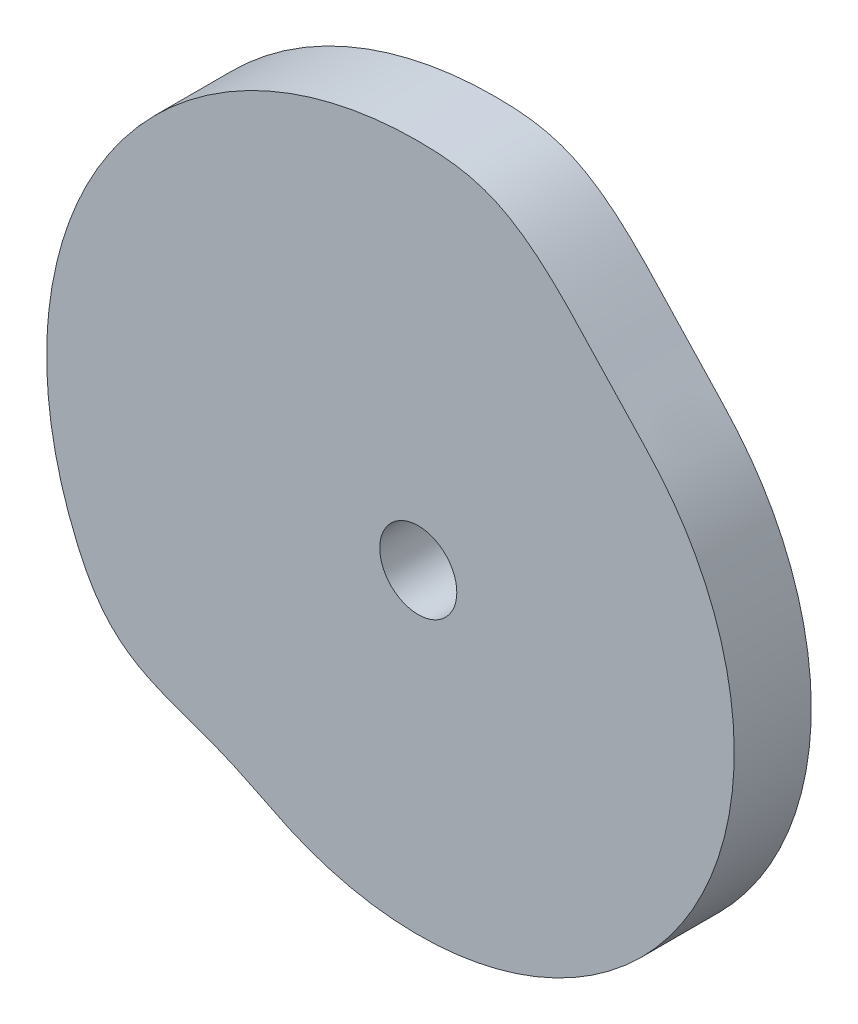
SolidWorks part; units mm, degrees
ref_plane "前视基准面" through (0, 0, 0) normal (0, 0, 1) x (1, 0, 0)
ref_plane "上视基准面" through (0, 0, 0) normal (0, 1, 0) x (1, 0, 0)
ref_plane "右视基准面" through (0, 0, 0) normal (1, 0, 0) x (0, 0, -1)
other "Configuration Table"
curve "曲线1"
sketch "草图1" plane through (0, 0, 0) normal (0, 0, 1) x (1, 0, 0)
  circle A0 centre (0, 0) radius 10
  spline S0 degree 3 poles (-96.3975, 3.0479) (-96.4204, 2.2065) (-96.436, 1.365) (-96.4444, 0.5234) (-96.4451, -0.3182) (-96.4388, -1.1598) (-96.4249, -2.0013) (-96.4039, -2.8427) (-96.3753, -3.6839) (-96.3396, -4.5247) (-96.2963, -5.3653) (-96.2458, -6.2054) (-96.188, -7.0451) (-96.1229, -7.8842) (-96.0504, -8.7227) (-95.9706, -9.5606) (-95.8837, -10.3977) (-95.7892, -11.2341) (-95.6875, -12.0695) (-95.5785, -12.9041) (-95.4623, -13.7377) (-95.3388, -14.5702) (-95.208, -15.4016) (-95.07, -16.2319) (-94.9247, -17.0609) (-94.7722, -17.8886) (-94.6125, -18.7149) (-94.4456, -19.5399) (-94.2715, -20.3633) (-94.0902, -21.1852) (-93.9017, -22.0055) (-93.7061, -22.8241) (-93.5034, -23.6409) (-93.2935, -24.456) (-93.0765, -25.2692) (-92.8525, -26.0805) (-92.6214, -26.8898) (-92.3832, -27.697) (-92.138, -28.5022) (-91.8856, -29.3051) (-91.6265, -30.1058) (-91.3603, -30.9043) (-91.087, -31.7003) (-90.807, -32.494) (-90.52, -33.2852) (-90.226, -34.0739) (-89.9252, -34.8599) (-89.6176, -35.6433) (-89.3033, -36.4241) (-88.9819, -37.202) (-88.654, -37.9769) (-88.32, -38.7472) (-87.9811, -39.5106) (-87.638, -40.2642) (-87.2906, -41.0062) (-86.9387, -41.736) (-86.582, -42.4534) (-86.22, -43.1582) (-85.8525, -43.8499) (-85.4791, -44.5285) (-85.0995, -45.1937) (-84.7136, -45.8455) (-84.3208, -46.4835) (-83.9213, -47.108) (-83.5147, -47.7187) (-83.1006, -48.3157) (-82.6792, -48.8991) (-82.25, -49.4688) (-81.813, -50.0249) (-81.368, -50.5676) (-80.9151, -51.0971) (-80.4537, -51.6134) (-79.984, -52.1168) (-79.5057, -52.6074) (-79.019, -53.0854) (-78.5234, -53.5509) (-78.0192, -54.0044) (-77.506, -54.4458) (-76.9839, -54.8755) (-76.4529, -55.2938) (-75.9129, -55.7006) (-75.364, -56.0965) (-74.8061, -56.4816) (-74.2393, -56.856) (-73.6637, -57.2203) (-73.0793, -57.5745) (-72.4862, -57.9192) (-71.8844, -58.2545) (-71.2741, -58.5807) (-70.6555, -58.8985) (-70.0286, -59.208) (-69.3936, -59.5099) (-68.7506, -59.8044) (-68.0997, -60.0924) (-67.441, -60.3741) (-66.7748, -60.6502) (-66.1012, -60.9213) (-65.4203, -61.1881) (-64.7323, -61.4512) (-64.0373, -61.7112) (-63.3356, -61.9692) (-62.6273, -62.2254) (-61.9126, -62.481) (-61.1919, -62.7366) (-60.4653, -62.9927) (-59.7332, -63.2503) (-58.9961, -63.5102) (-58.2542, -63.7729) (-57.508, -64.0391) (-56.758, -64.3093) (-56.0048, -64.5842) (-55.2488, -64.8641) (-54.4907, -65.1494) (-53.7312, -65.4406) (-52.9708, -65.7379) (-52.2102, -66.041) (-51.45, -66.3504) (-50.6909, -66.6659) (-49.9333, -66.9872) (-49.1779, -67.3142) (-48.425, -67.6464) (-47.6753, -67.9837) (-46.9291, -68.3253) (-46.1866, -68.6711) (-45.4482, -69.0201) (-44.7141, -69.3718) (-43.9844, -69.7256) (-43.2593, -70.0809) (-42.5389, -70.4368) (-41.8233, -70.7929) (-41.1124, -71.148) (-40.4064, -71.5018) (-39.7052, -71.8534) (-39.0089, -72.2018) (-38.3174, -72.5464) (-37.631, -72.8867) (-36.9495, -73.2216) (-36.2729, -73.5506) (-35.6015, -73.8729) (-34.9353, -74.1878) (-34.2743, -74.4947) (-33.6171, -74.7934) (-32.9613, -75.0848) (-32.3045, -75.3696) (-31.6456, -75.6488) (-30.9842, -75.9219) (-30.3205, -76.1895) (-29.6545, -76.4512) (-28.9862, -76.7071) (-28.3157, -76.9571) (-27.6431, -77.2013) (-26.9683, -77.4395) (-26.2915, -77.6719) (-25.6127, -77.8984) (-24.9319, -78.1189) (-24.2493, -78.3335) (-23.5648, -78.5422) (-22.8785, -78.7448) (-22.1905, -78.9416) (-21.5007, -79.1321) (-20.8093, -79.3167) (-20.1164, -79.4953) (-19.4219, -79.6678) (-18.7259, -79.8342) (-18.0286, -79.9946) (-17.3298, -80.1489) (-16.6297, -80.2971) (-15.9284, -80.4391) (-15.2258, -80.5751) (-14.5221, -80.7049) (-13.8173, -80.8285) (-13.1114, -80.946) (-12.4045, -81.0575) (-11.6966, -81.1625) (-10.988, -81.2615) (-10.2784, -81.3543) (-9.5681, -81.4409) (-8.857, -81.5213) (-8.1453, -81.5956) (-7.4329, -81.6634) (-6.72, -81.7253) (-6.0066, -81.7807) (-5.2927, -81.83) (-4.5784, -81.8732) (-3.8637, -81.9099) (-3.1488, -81.9405) (-2.4336, -81.965) (-1.7183, -81.983) (-1.0028, -81.995) (-0.2872, -82.0005) (0.4284, -82) (1.1439, -81.993) (1.8594, -81.9799) (2.5747, -81.9607) (3.2899, -81.935) (4.0048, -81.9033) (4.7193, -81.8651) (5.4336, -81.8208) (6.1474, -81.7704) (6.8607, -81.7135) (7.5735, -81.6505) (8.2858, -81.5813) (8.9974, -81.5059) (9.7083, -81.4243) (10.4185, -81.3365) (11.1279, -81.2425) (11.8364, -81.1423) (12.5441, -81.0359) (13.2507, -80.9233) (13.9564, -80.8046) (14.661, -80.6797) (15.3645, -80.5487) (16.0668, -80.4116) (16.7679, -80.2683) (17.4677, -80.1189) (18.1662, -79.9636) (18.8634, -79.8019) (19.559, -79.6342) (20.2532, -79.4605) (20.9459, -79.2808) (21.637, -79.095) (22.3263, -78.9031) (23.014, -78.7053) (23.7, -78.5015) (24.3841, -78.2917) (25.0664, -78.0759) (25.7468, -77.8542) (26.4253, -77.6266) (27.1016, -77.393) (27.7759, -77.1535) (28.4482, -76.9082) (29.1182, -76.657) (29.7861, -76.3999) (30.4517, -76.1372) (31.1149, -75.8685) (31.7758, -75.5942) (32.4342, -75.3139) (33.0902, -75.0281) (33.7437, -74.7365) (34.3946, -74.4391) (35.0429, -74.1361) (35.6886, -73.8276) (36.3314, -73.5132) (36.9716, -73.1934) (37.6089, -72.868) (38.2434, -72.537) (38.8749, -72.2005) (39.5035, -71.8585) (40.1291, -71.5111) (40.7515, -71.1581) (41.3709, -70.7998) (41.9872, -70.4361) (42.6002, -70.0669) (43.2101, -69.6926) (43.8167, -69.3129) (44.4199, -68.9279) (45.0196, -68.5376) (45.616, -68.1422) (46.2089, -67.7414) (46.7983, -67.3357) (47.3841, -66.9246) (47.9663, -66.5086) (48.5449, -66.0875) (49.1198, -65.6615) (49.6909, -65.2302) (50.2582, -64.7941) (50.8218, -64.3531) (51.3814, -63.9071) (51.9371, -63.4563) (52.489, -63.0007) (53.0367, -62.5401) (53.5805, -62.075) (54.1201, -61.6051) (54.6556, -61.1305) (55.187, -60.6512) (55.7142, -60.1673) (56.2371, -59.6788) (56.7557, -59.1857) (57.2701, -58.6883) (57.78, -58.1862) (58.2857, -57.6799) (58.7867, -57.1689) (59.2834, -56.6538) (59.7756, -56.1344) (60.263, -55.6105) (60.7461, -55.0825) (61.2245, -54.5503) (61.6982, -54.014) (62.1672, -53.4735) (62.6315, -52.929) (63.0909, -52.3803) (63.5456, -51.8278) (63.9955, -51.2713) (64.4405, -50.7109) (64.8805, -50.1466) (65.3158, -49.5786) (65.7458, -49.0066) (66.171, -48.431) (66.5912, -47.8518) (67.0061, -47.2688) (67.4162, -46.6823) (67.821, -46.0922) (68.2206, -45.4986) (68.615, -44.9015) (69.0043, -44.3011) (69.3882, -43.6972) (69.7669, -43.09) (70.1403, -42.4796) (70.5083, -41.8659) (70.8709, -41.249) (71.2282, -40.629) (71.58, -40.0058) (71.9264, -39.3797) (72.2673, -38.7505) (72.6027, -38.1184) (72.9327, -37.4834) (73.2569, -36.8454) (73.5757, -36.2048) (73.8888, -35.5613) (74.1963, -34.9152) (74.4982, -34.2664) (74.7945, -33.615) (75.0848, -32.961) (75.3696, -32.3045) (75.6488, -31.6456) (75.9219, -30.9842) (76.1895, -30.3205) (76.4512, -29.6545) (76.7071, -28.9862) (76.9571, -28.3157) (77.2013, -27.6431) (77.4395, -26.9683) (77.6719, -26.2915) (77.8984, -25.6127) (78.1189, -24.9319) (78.3335, -24.2493) (78.5422, -23.5648) (78.7448, -22.8785) (78.9416, -22.1905) (79.1321, -21.5007) (79.3167, -20.8093) (79.4953, -20.1164) (79.6678, -19.4219) (79.8342, -18.7259) (79.9946, -18.0286) (80.1489, -17.3298) (80.2971, -16.6297) (80.4391, -15.9284) (80.5751, -15.2258) (80.7049, -14.5221) (80.8285, -13.8173) (80.946, -13.1114) (81.0575, -12.4045) (81.1625, -11.6966) (81.2615, -10.988) (81.3543, -10.2784) (81.4409, -9.5681) (81.5213, -8.857) (81.5956, -8.1453) (81.6634, -7.4329) (81.7253, -6.72) (81.7807, -6.0066) (81.83, -5.2927) (81.8732, -4.5784) (81.9099, -3.8637) (81.9405, -3.1488) (81.965, -2.4336) (81.983, -1.7183) (81.995, -1.0028) (82.0005, -0.2872) (82, 0.4284) (81.993, 1.1439) (81.9799, 1.8594) (81.9607, 2.5747) (81.935, 3.2899) (81.9033, 4.0048) (81.8651, 4.7193) (81.8208, 5.4336) (81.7704, 6.1474) (81.7135, 6.8607) (81.6505, 7.5735) (81.5813, 8.2858) (81.5059, 8.9974) (81.4243, 9.7083) (81.3365, 10.4185) (81.2425, 11.1279) (81.1423, 11.8364) (81.0359, 12.5441) (80.9233, 13.2507) (80.8046, 13.9564) (80.6797, 14.661) (80.5487, 15.3645) (80.4116, 16.0668) (80.2683, 16.7679) (80.1189, 17.4677) (79.9636, 18.1662) (79.8019, 18.8634) (79.6342, 19.559) (79.4605, 20.2532) (79.2808, 20.9459) (79.095, 21.637) (78.9031, 22.3263) (78.7053, 23.014) (78.5015, 23.7) (78.2917, 24.3841) (78.0759, 25.0664) (77.8542, 25.7468) (77.6266, 26.4253) (77.393, 27.1016) (77.1535, 27.7759) (76.9082, 28.4482) (76.657, 29.1182) (76.3999, 29.7861) (76.1372, 30.4517) (75.8685, 31.1149) (75.5942, 31.7758) (75.3139, 32.4342) (75.0281, 33.0902) (74.7365, 33.7437) (74.4391, 34.3946) (74.1361, 35.0429) (73.8276, 35.6886) (73.5132, 36.3314) (73.1934, 36.9716) (72.868, 37.6089) (72.537, 38.2434) (72.2005, 38.8749) (71.8585, 39.5035) (71.5111, 40.1291) (71.1581, 40.7515) (70.7998, 41.3709) (70.4361, 41.9872) (70.0669, 42.6002) (69.6926, 43.2101) (69.3129, 43.8167) (68.9279, 44.4199) (68.5376, 45.0196) (68.1422, 45.616) (67.7414, 46.2089) (67.3357, 46.7983) (66.9246, 47.3841) (66.5086, 47.9663) (66.0875, 48.5449) (65.6615, 49.1198) (65.2302, 49.6909) (64.7941, 50.2582) (64.3531, 50.8218) (63.9071, 51.3814) (63.4563, 51.9371) (63.0007, 52.489) (62.54, 53.0368) (62.0735, 53.5821) (61.5992, 54.1268) (61.1156, 54.6733) (60.6221, 55.2236) (60.1186, 55.778) (59.6054, 56.337) (59.0831, 56.9013) (58.5518, 57.4709) (58.012, 58.0463) (57.4641, 58.6278) (56.9085, 59.2155) (56.3456, 59.8099) (55.7757, 60.4108) (55.1994, 61.0185) (54.6172, 61.6331) (54.0292, 62.2545) (53.4358, 62.8827) (52.8376, 63.5178) (52.2346, 64.1594) (51.6273, 64.8077) (51.0156, 65.4621) (50.4003, 66.1229) (49.781, 66.7894) (49.1582, 67.4614) (48.532, 68.1386) (47.9026, 68.8206) (47.27, 69.507) (46.6341, 70.1972) (45.9953, 70.8909) (45.3535, 71.5875) (44.7089, 72.2863) (44.0614, 72.9868) (43.411, 73.6883) (42.7579, 74.3902) (42.1022, 75.0918) (41.4437, 75.7921) (40.7827, 76.4908) (40.1192, 77.1867) (39.4532, 77.8791) (38.7848, 78.5672) (38.1142, 79.2501) (37.4415, 79.9271) (36.7666, 80.5971) (36.09, 81.2596) (35.4115, 81.9133) (34.7313, 82.5577) (34.0495, 83.1918) (33.3665, 83.815) (32.6821, 84.4261) (31.9968, 85.025) (31.3104, 85.6105) (30.6233, 86.1823) (29.9354, 86.7394) (29.2471, 87.2816) (28.5583, 87.8082) (27.8692, 88.319) (27.1798, 88.8133) (26.4902, 89.2912) (25.8004, 89.7522) (25.1105, 90.196) (24.4202, 90.6228) (23.7297, 91.0325) (23.0386, 91.4249) (22.347, 91.8004) (21.6545, 92.1588) (20.9611, 92.5004) (20.2662, 92.8252) (19.5698, 93.1338) (18.8713, 93.4261) (18.1705, 93.7026) (17.467, 93.9634) (16.7602, 94.2089) (16.0499, 94.4394) (15.3355, 94.6552) (14.6167, 94.8568) (13.8929, 95.0442) (13.1637, 95.2181) (12.4288, 95.3784) (11.6877, 95.5259) (10.94, 95.6607) (10.1855, 95.7829) (9.4237, 95.8936) (8.6544, 95.9924) (7.8773, 96.0803) (7.0922, 96.1572) (6.2987, 96.2241) (5.4969, 96.2809) (4.6864, 96.3285) (3.8672, 96.3672) (3.0394, 96.3979) (2.2043, 96.4204) (1.3648, 96.436) (0.5234, 96.4444) (-0.3182, 96.4451) (-1.1598, 96.4388) (-2.0013, 96.4249) (-2.8427, 96.4039) (-3.6839, 96.3753) (-4.5247, 96.3396) (-5.3653, 96.2963) (-6.2054, 96.2458) (-7.0451, 96.188) (-7.8842, 96.1229) (-8.7227, 96.0504) (-9.5606, 95.9706) (-10.3977, 95.8837) (-11.2341, 95.7892) (-12.0695, 95.6875) (-12.9041, 95.5785) (-13.7377, 95.4623) (-14.5702, 95.3388) (-15.4016, 95.208) (-16.2319, 95.07) (-17.0609, 94.9247) (-17.8886, 94.7722) (-18.7149, 94.6125) (-19.5399, 94.4456) (-20.3633, 94.2715) (-21.1852, 94.0902) (-22.0055, 93.9017) (-22.8241, 93.7061) (-23.6409, 93.5034) (-24.456, 93.2935) (-25.2692, 93.0765) (-26.0805, 92.8525) (-26.8898, 92.6214) (-27.697, 92.3832) (-28.5022, 92.138) (-29.3051, 91.8856) (-30.1058, 91.6265) (-30.9043, 91.3603) (-31.7003, 91.087) (-32.494, 90.807) (-33.2852, 90.52) (-34.0739, 90.226) (-34.8599, 89.9252) (-35.6433, 89.6176) (-36.4241, 89.3033) (-37.202, 88.9819) (-37.9771, 88.654) (-38.7492, 88.3191) (-39.5185, 87.9776) (-40.2847, 87.6294) (-41.0479, 87.2745) (-41.8079, 86.913) (-42.5648, 86.5449) (-43.3184, 86.1701) (-44.0687, 85.7888) (-44.8157, 85.401) (-45.5592, 85.0067) (-46.2993, 84.6059) (-47.0359, 84.1986) (-47.7688, 83.7848) (-48.4982, 83.3648) (-49.2238, 82.9385) (-49.9457, 82.5058) (-50.6637, 82.0667) (-51.3781, 81.6216) (-52.0883, 81.17) (-52.7947, 80.7124) (-53.497, 80.2486) (-54.1953, 79.7787) (-54.8894, 79.3028) (-55.5793, 78.8207) (-56.265, 78.3327) (-56.9465, 77.8388) (-57.6235, 77.3388) (-58.2963, 76.8331) (-58.9645, 76.3214) (-59.6284, 75.804) (-60.2875, 75.2806) (-60.9422, 74.7518) (-61.5922, 74.217) (-62.2375, 73.6767) (-62.8781, 73.1308) (-63.5139, 72.5793) (-64.1448, 72.0223) (-64.7709, 71.4598) (-65.3921, 70.8919) (-66.0081, 70.3185) (-66.6192, 69.7398) (-67.2253, 69.1558) (-67.8263, 68.5665) (-68.4221, 67.9721) (-69.0126, 67.3723) (-69.5979, 66.7675) (-70.1779, 66.1577) (-70.7525, 65.5427) (-71.3218, 64.9229) (-71.8856, 64.2979) (-72.444, 63.6682) (-72.9968, 63.0336) (-73.5442, 62.3942) (-74.0858, 61.75) (-74.6218, 61.1011) (-75.1523, 60.4477) (-75.6768, 59.7894) (-76.1958, 59.1269) (-76.7087, 58.4596) (-77.2161, 57.7881) (-77.7174, 57.112) (-78.2128, 56.4316) (-78.7023, 55.7469) (-79.1858, 55.058) (-79.6632, 54.3649) (-80.1347, 53.6677) (-80.5999, 52.9663) (-81.0591, 52.2609) (-81.512, 51.5516) (-81.9588, 50.8383) (-82.3992, 50.1211) (-82.8336, 49.4002) (-83.2614, 48.6754) (-83.6831, 47.947) (-84.0982, 47.2149) (-84.5071, 46.4793) (-84.9095, 45.74) (-85.3053, 44.9972) (-85.6949, 44.2512) (-86.0776, 43.5016) (-86.4542, 42.7489) (-86.8237, 41.9927) (-87.187, 41.2335) (-87.5435, 40.4711) (-87.8933, 39.7056) (-88.2366, 38.9371) (-88.5729, 38.1656) (-88.9026, 37.3912) (-89.2255, 36.614) (-89.5416, 35.834) (-89.851, 35.0513) (-90.1533, 34.2658) (-90.4489, 33.4778) (-90.7377, 32.6872) (-91.0195, 31.8941) (-91.2942, 31.0986) (-91.5622, 30.3007) (-91.8232, 29.5006) (-92.0771, 28.6982) (-92.324, 27.8936) (-92.5639, 27.0868) (-92.7968, 26.278) (-93.0226, 25.4672) (-93.2413, 24.6545) (-93.4527, 23.8399) (-93.6573, 23.0235) (-93.8547, 22.2053) (-94.0449, 21.3854) (-94.2279, 20.5639) (-94.4039, 19.7408) (-94.5724, 18.9162) (-94.7339, 18.0902) (-94.8882, 17.2629) (-95.0352, 16.4342) (-95.175, 15.6042) (-95.3075, 14.7731) (-95.4328, 13.9408) (-95.5508, 13.1075) (-95.6617, 12.2731) (-95.765, 11.4379) (-95.8612, 10.6017) (-95.9502, 9.7648) (-96.0316, 8.9271) (-96.106, 8.0888) (-96.1728, 7.2498) (-96.2324, 6.4103) (-96.2847, 5.5702) (-96.3296, 4.7298) (-96.3672, 3.8889) (-96.3975, 3.0479) (-96.4204, 2.2065) (-96.436, 1.365) knots -0.004514 -0.003009 -0.001505 0 0.001505 0.003009 0.004514 0.006018 0.007523 0.009027 0.010532 0.012036 0.013541 0.015045 0.01655 0.018054 0.019559 0.021064 0.022568 0.024073 0.025577 0.027082 0.028586 0.030091 0.031595 0.0331 0.034604 0.036109 0.037613 0.039118 0.040623 0.042127 0.043632 0.045136 0.046641 0.048145 0.04965 0.051154 0.052659 0.054164 0.055668 0.057173 0.058677 0.060182 0.061686 0.063191 0.064695 0.0662 0.067704 0.069209 0.070713 0.072218 0.073723 0.075226 0.076721 0.078202 0.079666 0.081115 0.082547 0.083963 0.085363 0.086748 0.088117 0.089471 0.09081 0.092135 0.093446 0.094744 0.096031 0.097305 0.098569 0.099824 0.101069 0.102306 0.103537 0.104761 0.10598 0.107195 0.108407 0.109617 0.110825 0.112033 0.113241 0.114451 0.115662 0.116876 0.118094 0.119315 0.120541 0.121772 0.123009 0.124252 0.125502 0.126759 0.128023 0.129295 0.130575 0.131864 0.133162 0.13447 0.135786 0.137113 0.138449 0.139796 0.141152 0.142519 0.143897 0.145284 0.146682 0.148089 0.149505 0.15093 0.152364 0.153805 0.155253 0.156708 0.158168 0.159631 0.161099 0.162569 0.16404 0.165512 0.166983 0.168453 0.169921 0.171385 0.172845 0.174301 0.175751 0.177195 0.178631 0.18006 0.181481 0.182893 0.184295 0.185687 0.187069 0.188438 0.189796 0.191141 0.192473 0.19379 0.195093 0.196381 0.197662 0.198941 0.20022 0.2015 0.202779 0.204058 0.205337 0.206616 0.207896 0.209175 0.210454 0.211733 0.213013 0.214292 0.215571 0.21685 0.218129 0.219409 0.220688 0.221967 0.223246 0.224525 0.225805 0.227084 0.228363 0.229642 0.230921 0.232201 0.23348 0.234759 0.236038 0.237318 0.238597 0.239876 0.241155 0.242434 0.243713 0.244993 0.246272 0.247551 0.24883 0.25011 0.251389 0.252668 0.253947 0.255226 0.256506 0.257785 0.259064 0.260343 0.261622 0.262902 0.264181 0.26546 0.266739 0.268018 0.269298 0.270577 0.271856 0.273135 0.274415 0.275694 0.276973 0.278252 0.279531 0.280811 0.28209 0.283369 0.284648 0.285927 0.287207 0.288486 0.289765 0.291044 0.292323 0.293603 0.294882 0.296161 0.29744 0.29872 0.299999 0.301278 0.302557 0.303836 0.305116 0.306395 0.307674 0.308953 0.310232 0.311512 0.312791 0.31407 0.315349 0.316628 0.317907 0.319187 0.320466 0.321745 0.323024 0.324304 0.325583 0.326862 0.328141 0.32942 0.3307 0.331979 0.333258 0.334537 0.335816 0.337096 0.338375 0.339654 0.340933 0.342213 0.343492 0.344771 0.34605 0.347329 0.348609 0.349888 0.351167 0.352446 0.353725 0.355005 0.356284 0.357563 0.358842 0.360121 0.361401 0.36268 0.363959 0.365238 0.366517 0.367797 0.369076 0.370355 0.371634 0.372913 0.374193 0.375472 0.376751 0.37803 0.379309 0.380589 0.381868 0.383147 0.384426 0.385706 0.386985 0.388264 0.389543 0.390822 0.392102 0.393381 0.39466 0.395939 0.397218 0.398498 0.399777 0.401056 0.402335 0.403614 0.404894 0.406173 0.407452 0.408731 0.410011 0.41129 0.412569 0.413848 0.415127 0.416407 0.417686 0.418965 0.420244 0.421523 0.422803 0.424082 0.425361 0.42664 0.427919 0.429199 0.430478 0.431757 0.433036 0.434315 0.435595 0.436874 0.438153 0.439432 0.440711 0.441991 0.44327 0.444549 0.445828 0.447107 0.448387 0.449666 0.450945 0.452224 0.453503 0.454783 0.456062 0.457341 0.45862 0.459899 0.461179 0.462458 0.463737 0.465016 0.466296 0.467575 0.468854 0.470133 0.471412 0.472692 0.473971 0.47525 0.476529 0.477808 0.479088 0.480367 0.481646 0.482925 0.484204 0.485484 0.486763 0.488042 0.489321 0.4906 0.49188 0.493159 0.494438 0.495717 0.496997 0.498276 0.499555 0.500834 0.502113 0.503393 0.504672 0.505951 0.50723 0.508509 0.509789 0.511068 0.512347 0.513626 0.514905 0.516185 0.517464 0.518743 0.520022 0.521301 0.522581 0.52386 0.525139 0.526418 0.527698 0.528977 0.530256 0.531535 0.532814 0.534094 0.535373 0.536652 0.537931 0.53921 0.54049 0.541769 0.543048 0.544327 0.545606 0.546886 0.548165 0.549444 0.550723 0.552002 0.553282 0.554561 0.55584 0.557119 0.558398 0.559678 0.560957 0.562236 0.563515 0.564795 0.566074 0.567353 0.568632 0.569911 0.571191 0.57247 0.573749 0.575028 0.576307 0.577587 0.578866 0.580145 0.581424 0.582703 0.583983 0.585262 0.586541 0.58782 0.5891 0.590379 0.591658 0.592938 0.594227 0.595531 0.596852 0.598191 0.599547 0.600922 0.602314 0.603725 0.605153 0.606599 0.608063 0.609543 0.61104 0.612554 0.614083 0.615628 0.617188 0.618763 0.620351 0.621952 0.623567 0.625193 0.626831 0.62848 0.630139 0.631808 0.633486 0.635172 0.636866 0.638566 0.640271 0.641982 0.643696 0.645413 0.647132 0.648851 0.650571 0.652288 0.654004 0.655715 0.657422 0.659122 0.660815 0.6625 0.664175 0.66584 0.667493 0.669133 0.670761 0.672374 0.673972 0.675554 0.677121 0.678671 0.680204 0.68172 0.68322 0.684703 0.686169 0.68762 0.689055 0.690475 0.691882 0.693275 0.694656 0.696027 0.697388 0.698741 0.700087 0.701428 0.702765 0.704099 0.705433 0.706767 0.708103 0.709442 0.710787 0.712137 0.713495 0.714861 0.716236 0.717622 0.71902 0.72043 0.721853 0.72329 0.724741 0.726207 0.727688 0.729184 0.730687 0.732192 0.733696 0.735201 0.736705 0.73821 0.739714 0.741219 0.742723 0.744228 0.745732 0.747237 0.748741 0.750246 0.751751 0.753255 0.75476 0.756264 0.757769 0.759273 0.760778 0.762282 0.763787 0.765291 0.766796 0.7683 0.769805 0.771309 0.772814 0.774319 0.775823 0.777328 0.778832 0.780337 0.781841 0.783346 0.78485 0.786355 0.787859 0.789364 0.790869 0.792373 0.793878 0.795382 0.796887 0.798391 0.799896 0.8014 0.802905 0.804409 0.805914 0.807419 0.808923 0.810428 0.811932 0.813437 0.814941 0.816446 0.81795 0.819455 0.82096 0.822464 0.823968 0.825473 0.826978 0.828482 0.829987 0.831491 0.832996 0.8345 0.836005 0.837509 0.839014 0.840518 0.842023 0.843527 0.845032 0.846537 0.848041 0.849546 0.85105 0.852555 0.854059 0.855564 0.857069 0.858573 0.860078 0.861582 0.863087 0.864591 0.866096 0.8676 0.869105 0.870609 0.872114 0.873618 0.875123 0.876627 0.878132 0.879637 0.881141 0.882646 0.88415 0.885655 0.887159 0.888664 0.890168 0.891673 0.893178 0.894682 0.896187 0.897691 0.899196 0.9007 0.902205 0.903709 0.905214 0.906718 0.908223 0.909727 0.911232 0.912737 0.914241 0.915746 0.91725 0.918755 0.920259 0.921764 0.923268 0.924773 0.926277 0.927782 0.929286 0.930791 0.932296 0.9338 0.935305 0.936809 0.938314 0.939818 0.941323 0.942827 0.944332 0.945836 0.947341 0.948845 0.95035 0.951855 0.953359 0.954864 0.956368 0.957873 0.959377 0.960882 0.962386 0.963891 0.965396 0.9669 0.968405 0.969909 0.971414 0.972918 0.974423 0.975927 0.977432 0.978936 0.980441 0.981945 0.98345 0.984955 0.986459 0.987964 0.989468 0.990973 0.992477 0.993982 0.995486 0.996991 0.998495 1 1.001505 1.003009 1.004514 only from (-96.4192, 2.2065) to (-96.4192, 2.2065) construction
  spline S1 degree 3 poles (-96.3975, 3.0479) (-96.4204, 2.2065) (-96.436, 1.365) (-96.4444, 0.5234) (-96.4451, -0.3182) (-96.4388, -1.1598) (-96.4249, -2.0013) (-96.4039, -2.8427) (-96.3753, -3.6839) (-96.3396, -4.5247) (-96.2963, -5.3653) (-96.2458, -6.2054) (-96.188, -7.0451) (-96.1229, -7.8842) (-96.0504, -8.7227) (-95.9706, -9.5606) (-95.8837, -10.3977) (-95.7892, -11.2341) (-95.6875, -12.0695) (-95.5785, -12.9041) (-95.4623, -13.7377) (-95.3388, -14.5702) (-95.208, -15.4016) (-95.07, -16.2319) (-94.9247, -17.0609) (-94.7722, -17.8886) (-94.6125, -18.7149) (-94.4456, -19.5399) (-94.2715, -20.3633) (-94.0902, -21.1852) (-93.9017, -22.0055) (-93.7061, -22.8241) (-93.5034, -23.6409) (-93.2935, -24.456) (-93.0765, -25.2692) (-92.8525, -26.0805) (-92.6214, -26.8898) (-92.3832, -27.697) (-92.138, -28.5022) (-91.8856, -29.3051) (-91.6265, -30.1058) (-91.3603, -30.9043) (-91.087, -31.7003) (-90.807, -32.494) (-90.52, -33.2852) (-90.226, -34.0739) (-89.9252, -34.8599) (-89.6176, -35.6433) (-89.3033, -36.4241) (-88.9819, -37.202) (-88.654, -37.9769) (-88.32, -38.7472) (-87.9811, -39.5106) (-87.638, -40.2642) (-87.2906, -41.0062) (-86.9387, -41.736) (-86.582, -42.4534) (-86.22, -43.1582) (-85.8525, -43.8499) (-85.4791, -44.5285) (-85.0995, -45.1937) (-84.7136, -45.8455) (-84.3208, -46.4835) (-83.9213, -47.108) (-83.5147, -47.7187) (-83.1006, -48.3157) (-82.6792, -48.8991) (-82.25, -49.4688) (-81.813, -50.0249) (-81.368, -50.5676) (-80.9151, -51.0971) (-80.4537, -51.6134) (-79.984, -52.1168) (-79.5057, -52.6074) (-79.019, -53.0854) (-78.5234, -53.5509) (-78.0192, -54.0044) (-77.506, -54.4458) (-76.9839, -54.8755) (-76.4529, -55.2938) (-75.9129, -55.7006) (-75.364, -56.0965) (-74.8061, -56.4816) (-74.2393, -56.856) (-73.6637, -57.2203) (-73.0793, -57.5745) (-72.4862, -57.9192) (-71.8844, -58.2545) (-71.2741, -58.5807) (-70.6555, -58.8985) (-70.0286, -59.208) (-69.3936, -59.5099) (-68.7506, -59.8044) (-68.0997, -60.0924) (-67.441, -60.3741) (-66.7748, -60.6502) (-66.1012, -60.9213) (-65.4203, -61.1881) (-64.7323, -61.4512) (-64.0373, -61.7112) (-63.3356, -61.9692) (-62.6273, -62.2254) (-61.9126, -62.481) (-61.1919, -62.7366) (-60.4653, -62.9927) (-59.7332, -63.2503) (-58.9961, -63.5102) (-58.2542, -63.7729) (-57.508, -64.0391) (-56.758, -64.3093) (-56.0048, -64.5842) (-55.2488, -64.8641) (-54.4907, -65.1494) (-53.7312, -65.4406) (-52.9708, -65.7379) (-52.2102, -66.041) (-51.45, -66.3504) (-50.6909, -66.6659) (-49.9333, -66.9872) (-49.1779, -67.3142) (-48.425, -67.6464) (-47.6753, -67.9837) (-46.9291, -68.3253) (-46.1866, -68.6711) (-45.4482, -69.0201) (-44.7141, -69.3718) (-43.9844, -69.7256) (-43.2593, -70.0809) (-42.5389, -70.4368) (-41.8233, -70.7929) (-41.1124, -71.148) (-40.4064, -71.5018) (-39.7052, -71.8534) (-39.0089, -72.2018) (-38.3174, -72.5464) (-37.631, -72.8867) (-36.9495, -73.2216) (-36.2729, -73.5506) (-35.6015, -73.8729) (-34.9353, -74.1878) (-34.2743, -74.4947) (-33.6171, -74.7934) (-32.9613, -75.0848) (-32.3045, -75.3696) (-31.6456, -75.6488) (-30.9842, -75.9219) (-30.3205, -76.1895) (-29.6545, -76.4512) (-28.9862, -76.7071) (-28.3157, -76.9571) (-27.6431, -77.2013) (-26.9683, -77.4395) (-26.2915, -77.6719) (-25.6127, -77.8984) (-24.9319, -78.1189) (-24.2493, -78.3335) (-23.5648, -78.5422) (-22.8785, -78.7448) (-22.1905, -78.9416) (-21.5007, -79.1321) (-20.8093, -79.3167) (-20.1164, -79.4953) (-19.4219, -79.6678) (-18.7259, -79.8342) (-18.0286, -79.9946) (-17.3298, -80.1489) (-16.6297, -80.2971) (-15.9284, -80.4391) (-15.2258, -80.5751) (-14.5221, -80.7049) (-13.8173, -80.8285) (-13.1114, -80.946) (-12.4045, -81.0575) (-11.6966, -81.1625) (-10.988, -81.2615) (-10.2784, -81.3543) (-9.5681, -81.4409) (-8.857, -81.5213) (-8.1453, -81.5956) (-7.4329, -81.6634) (-6.72, -81.7253) (-6.0066, -81.7807) (-5.2927, -81.83) (-4.5784, -81.8732) (-3.8637, -81.9099) (-3.1488, -81.9405) (-2.4336, -81.965) (-1.7183, -81.983) (-1.0028, -81.995) (-0.2872, -82.0005) (0.4284, -82) (1.1439, -81.993) (1.8594, -81.9799) (2.5747, -81.9607) (3.2899, -81.935) (4.0048, -81.9033) (4.7193, -81.8651) (5.4336, -81.8208) (6.1474, -81.7704) (6.8607, -81.7135) (7.5735, -81.6505) (8.2858, -81.5813) (8.9974, -81.5059) (9.7083, -81.4243) (10.4185, -81.3365) (11.1279, -81.2425) (11.8364, -81.1423) (12.5441, -81.0359) (13.2507, -80.9233) (13.9564, -80.8046) (14.661, -80.6797) (15.3645, -80.5487) (16.0668, -80.4116) (16.7679, -80.2683) (17.4677, -80.1189) (18.1662, -79.9636) (18.8634, -79.8019) (19.559, -79.6342) (20.2532, -79.4605) (20.9459, -79.2808) (21.637, -79.095) (22.3263, -78.9031) (23.014, -78.7053) (23.7, -78.5015) (24.3841, -78.2917) (25.0664, -78.0759) (25.7468, -77.8542) (26.4253, -77.6266) (27.1016, -77.393) (27.7759, -77.1535) (28.4482, -76.9082) (29.1182, -76.657) (29.7861, -76.3999) (30.4517, -76.1372) (31.1149, -75.8685) (31.7758, -75.5942) (32.4342, -75.3139) (33.0902, -75.0281) (33.7437, -74.7365) (34.3946, -74.4391) (35.0429, -74.1361) (35.6886, -73.8276) (36.3314, -73.5132) (36.9716, -73.1934) (37.6089, -72.868) (38.2434, -72.537) (38.8749, -72.2005) (39.5035, -71.8585) (40.1291, -71.5111) (40.7515, -71.1581) (41.3709, -70.7998) (41.9872, -70.4361) (42.6002, -70.0669) (43.2101, -69.6926) (43.8167, -69.3129) (44.4199, -68.9279) (45.0196, -68.5376) (45.616, -68.1422) (46.2089, -67.7414) (46.7983, -67.3357) (47.3841, -66.9246) (47.9663, -66.5086) (48.5449, -66.0875) (49.1198, -65.6615) (49.6909, -65.2302) (50.2582, -64.7941) (50.8218, -64.3531) (51.3814, -63.9071) (51.9371, -63.4563) (52.489, -63.0007) (53.0367, -62.5401) (53.5805, -62.075) (54.1201, -61.6051) (54.6556, -61.1305) (55.187, -60.6512) (55.7142, -60.1673) (56.2371, -59.6788) (56.7557, -59.1857) (57.2701, -58.6883) (57.78, -58.1862) (58.2857, -57.6799) (58.7867, -57.1689) (59.2834, -56.6538) (59.7756, -56.1344) (60.263, -55.6105) (60.7461, -55.0825) (61.2245, -54.5503) (61.6982, -54.014) (62.1672, -53.4735) (62.6315, -52.929) (63.0909, -52.3803) (63.5456, -51.8278) (63.9955, -51.2713) (64.4405, -50.7109) (64.8805, -50.1466) (65.3158, -49.5786) (65.7458, -49.0066) (66.171, -48.431) (66.5912, -47.8518) (67.0061, -47.2688) (67.4162, -46.6823) (67.821, -46.0922) (68.2206, -45.4986) (68.615, -44.9015) (69.0043, -44.3011) (69.3882, -43.6972) (69.7669, -43.09) (70.1403, -42.4796) (70.5083, -41.8659) (70.8709, -41.249) (71.2282, -40.629) (71.58, -40.0058) (71.9264, -39.3797) (72.2673, -38.7505) (72.6027, -38.1184) (72.9327, -37.4834) (73.2569, -36.8454) (73.5757, -36.2048) (73.8888, -35.5613) (74.1963, -34.9152) (74.4982, -34.2664) (74.7945, -33.615) (75.0848, -32.961) (75.3696, -32.3045) (75.6488, -31.6456) (75.9219, -30.9842) (76.1895, -30.3205) (76.4512, -29.6545) (76.7071, -28.9862) (76.9571, -28.3157) (77.2013, -27.6431) (77.4395, -26.9683) (77.6719, -26.2915) (77.8984, -25.6127) (78.1189, -24.9319) (78.3335, -24.2493) (78.5422, -23.5648) (78.7448, -22.8785) (78.9416, -22.1905) (79.1321, -21.5007) (79.3167, -20.8093) (79.4953, -20.1164) (79.6678, -19.4219) (79.8342, -18.7259) (79.9946, -18.0286) (80.1489, -17.3298) (80.2971, -16.6297) (80.4391, -15.9284) (80.5751, -15.2258) (80.7049, -14.5221) (80.8285, -13.8173) (80.946, -13.1114) (81.0575, -12.4045) (81.1625, -11.6966) (81.2615, -10.988) (81.3543, -10.2784) (81.4409, -9.5681) (81.5213, -8.857) (81.5956, -8.1453) (81.6634, -7.4329) (81.7253, -6.72) (81.7807, -6.0066) (81.83, -5.2927) (81.8732, -4.5784) (81.9099, -3.8637) (81.9405, -3.1488) (81.965, -2.4336) (81.983, -1.7183) (81.995, -1.0028) (82.0005, -0.2872) (82, 0.4284) (81.993, 1.1439) (81.9799, 1.8594) (81.9607, 2.5747) (81.935, 3.2899) (81.9033, 4.0048) (81.8651, 4.7193) (81.8208, 5.4336) (81.7704, 6.1474) (81.7135, 6.8607) (81.6505, 7.5735) (81.5813, 8.2858) (81.5059, 8.9974) (81.4243, 9.7083) (81.3365, 10.4185) (81.2425, 11.1279) (81.1423, 11.8364) (81.0359, 12.5441) (80.9233, 13.2507) (80.8046, 13.9564) (80.6797, 14.661) (80.5487, 15.3645) (80.4116, 16.0668) (80.2683, 16.7679) (80.1189, 17.4677) (79.9636, 18.1662) (79.8019, 18.8634) (79.6342, 19.559) (79.4605, 20.2532) (79.2808, 20.9459) (79.095, 21.637) (78.9031, 22.3263) (78.7053, 23.014) (78.5015, 23.7) (78.2917, 24.3841) (78.0759, 25.0664) (77.8542, 25.7468) (77.6266, 26.4253) (77.393, 27.1016) (77.1535, 27.7759) (76.9082, 28.4482) (76.657, 29.1182) (76.3999, 29.7861) (76.1372, 30.4517) (75.8685, 31.1149) (75.5942, 31.7758) (75.3139, 32.4342) (75.0281, 33.0902) (74.7365, 33.7437) (74.4391, 34.3946) (74.1361, 35.0429) (73.8276, 35.6886) (73.5132, 36.3314) (73.1934, 36.9716) (72.868, 37.6089) (72.537, 38.2434) (72.2005, 38.8749) (71.8585, 39.5035) (71.5111, 40.1291) (71.1581, 40.7515) (70.7998, 41.3709) (70.4361, 41.9872) (70.0669, 42.6002) (69.6926, 43.2101) (69.3129, 43.8167) (68.9279, 44.4199) (68.5376, 45.0196) (68.1422, 45.616) (67.7414, 46.2089) (67.3357, 46.7983) (66.9246, 47.3841) (66.5086, 47.9663) (66.0875, 48.5449) (65.6615, 49.1198) (65.2302, 49.6909) (64.7941, 50.2582) (64.3531, 50.8218) (63.9071, 51.3814) (63.4563, 51.9371) (63.0007, 52.489) (62.54, 53.0368) (62.0735, 53.5821) (61.5992, 54.1268) (61.1156, 54.6733) (60.6221, 55.2236) (60.1186, 55.778) (59.6054, 56.337) (59.0831, 56.9013) (58.5518, 57.4709) (58.012, 58.0463) (57.4641, 58.6278) (56.9085, 59.2155) (56.3456, 59.8099) (55.7757, 60.4108) (55.1994, 61.0185) (54.6172, 61.6331) (54.0292, 62.2545) (53.4358, 62.8827) (52.8376, 63.5178) (52.2346, 64.1594) (51.6273, 64.8077) (51.0156, 65.4621) (50.4003, 66.1229) (49.781, 66.7894) (49.1582, 67.4614) (48.532, 68.1386) (47.9026, 68.8206) (47.27, 69.507) (46.6341, 70.1972) (45.9953, 70.8909) (45.3535, 71.5875) (44.7089, 72.2863) (44.0614, 72.9868) (43.411, 73.6883) (42.7579, 74.3902) (42.1022, 75.0918) (41.4437, 75.7921) (40.7827, 76.4908) (40.1192, 77.1867) (39.4532, 77.8791) (38.7848, 78.5672) (38.1142, 79.2501) (37.4415, 79.9271) (36.7666, 80.5971) (36.09, 81.2596) (35.4115, 81.9133) (34.7313, 82.5577) (34.0495, 83.1918) (33.3665, 83.815) (32.6821, 84.4261) (31.9968, 85.025) (31.3104, 85.6105) (30.6233, 86.1823) (29.9354, 86.7394) (29.2471, 87.2816) (28.5583, 87.8082) (27.8692, 88.319) (27.1798, 88.8133) (26.4902, 89.2912) (25.8004, 89.7522) (25.1105, 90.196) (24.4202, 90.6228) (23.7297, 91.0325) (23.0386, 91.4249) (22.347, 91.8004) (21.6545, 92.1588) (20.9611, 92.5004) (20.2662, 92.8252) (19.5698, 93.1338) (18.8713, 93.4261) (18.1705, 93.7026) (17.467, 93.9634) (16.7602, 94.2089) (16.0499, 94.4394) (15.3355, 94.6552) (14.6167, 94.8568) (13.8929, 95.0442) (13.1637, 95.2181) (12.4288, 95.3784) (11.6877, 95.5259) (10.94, 95.6607) (10.1855, 95.7829) (9.4237, 95.8936) (8.6544, 95.9924) (7.8773, 96.0803) (7.0922, 96.1572) (6.2987, 96.2241) (5.4969, 96.2809) (4.6864, 96.3285) (3.8672, 96.3672) (3.0394, 96.3979) (2.2043, 96.4204) (1.3648, 96.436) (0.5234, 96.4444) (-0.3182, 96.4451) (-1.1598, 96.4388) (-2.0013, 96.4249) (-2.8427, 96.4039) (-3.6839, 96.3753) (-4.5247, 96.3396) (-5.3653, 96.2963) (-6.2054, 96.2458) (-7.0451, 96.188) (-7.8842, 96.1229) (-8.7227, 96.0504) (-9.5606, 95.9706) (-10.3977, 95.8837) (-11.2341, 95.7892) (-12.0695, 95.6875) (-12.9041, 95.5785) (-13.7377, 95.4623) (-14.5702, 95.3388) (-15.4016, 95.208) (-16.2319, 95.07) (-17.0609, 94.9247) (-17.8886, 94.7722) (-18.7149, 94.6125) (-19.5399, 94.4456) (-20.3633, 94.2715) (-21.1852, 94.0902) (-22.0055, 93.9017) (-22.8241, 93.7061) (-23.6409, 93.5034) (-24.456, 93.2935) (-25.2692, 93.0765) (-26.0805, 92.8525) (-26.8898, 92.6214) (-27.697, 92.3832) (-28.5022, 92.138) (-29.3051, 91.8856) (-30.1058, 91.6265) (-30.9043, 91.3603) (-31.7003, 91.087) (-32.494, 90.807) (-33.2852, 90.52) (-34.0739, 90.226) (-34.8599, 89.9252) (-35.6433, 89.6176) (-36.4241, 89.3033) (-37.202, 88.9819) (-37.9771, 88.654) (-38.7492, 88.3191) (-39.5185, 87.9776) (-40.2847, 87.6294) (-41.0479, 87.2745) (-41.8079, 86.913) (-42.5648, 86.5449) (-43.3184, 86.1701) (-44.0687, 85.7888) (-44.8157, 85.401) (-45.5592, 85.0067) (-46.2993, 84.6059) (-47.0359, 84.1986) (-47.7688, 83.7848) (-48.4982, 83.3648) (-49.2238, 82.9385) (-49.9457, 82.5058) (-50.6637, 82.0667) (-51.3781, 81.6216) (-52.0883, 81.17) (-52.7947, 80.7124) (-53.497, 80.2486) (-54.1953, 79.7787) (-54.8894, 79.3028) (-55.5793, 78.8207) (-56.265, 78.3327) (-56.9465, 77.8388) (-57.6235, 77.3388) (-58.2963, 76.8331) (-58.9645, 76.3214) (-59.6284, 75.804) (-60.2875, 75.2806) (-60.9422, 74.7518) (-61.5922, 74.217) (-62.2375, 73.6767) (-62.8781, 73.1308) (-63.5139, 72.5793) (-64.1448, 72.0223) (-64.7709, 71.4598) (-65.3921, 70.8919) (-66.0081, 70.3185) (-66.6192, 69.7398) (-67.2253, 69.1558) (-67.8263, 68.5665) (-68.4221, 67.9721) (-69.0126, 67.3723) (-69.5979, 66.7675) (-70.1779, 66.1577) (-70.7525, 65.5427) (-71.3218, 64.9229) (-71.8856, 64.2979) (-72.444, 63.6682) (-72.9968, 63.0336) (-73.5442, 62.3942) (-74.0858, 61.75) (-74.6218, 61.1011) (-75.1523, 60.4477) (-75.6768, 59.7894) (-76.1958, 59.1269) (-76.7087, 58.4596) (-77.2161, 57.7881) (-77.7174, 57.112) (-78.2128, 56.4316) (-78.7023, 55.7469) (-79.1858, 55.058) (-79.6632, 54.3649) (-80.1347, 53.6677) (-80.5999, 52.9663) (-81.0591, 52.2609) (-81.512, 51.5516) (-81.9588, 50.8383) (-82.3992, 50.1211) (-82.8336, 49.4002) (-83.2614, 48.6754) (-83.6831, 47.947) (-84.0982, 47.2149) (-84.5071, 46.4793) (-84.9095, 45.74) (-85.3053, 44.9972) (-85.6949, 44.2512) (-86.0776, 43.5016) (-86.4542, 42.7489) (-86.8237, 41.9927) (-87.187, 41.2335) (-87.5435, 40.4711) (-87.8933, 39.7056) (-88.2366, 38.9371) (-88.5729, 38.1656) (-88.9026, 37.3912) (-89.2255, 36.614) (-89.5416, 35.834) (-89.851, 35.0513) (-90.1533, 34.2658) (-90.4489, 33.4778) (-90.7377, 32.6872) (-91.0195, 31.8941) (-91.2942, 31.0986) (-91.5622, 30.3007) (-91.8232, 29.5006) (-92.0771, 28.6982) (-92.324, 27.8936) (-92.5639, 27.0868) (-92.7968, 26.278) (-93.0226, 25.4672) (-93.2413, 24.6545) (-93.4527, 23.8399) (-93.6573, 23.0235) (-93.8547, 22.2053) (-94.0449, 21.3854) (-94.2279, 20.5639) (-94.4039, 19.7408) (-94.5724, 18.9162) (-94.7339, 18.0902) (-94.8882, 17.2629) (-95.0352, 16.4342) (-95.175, 15.6042) (-95.3075, 14.7731) (-95.4328, 13.9408) (-95.5508, 13.1075) (-95.6617, 12.2731) (-95.765, 11.4379) (-95.8612, 10.6017) (-95.9502, 9.7648) (-96.0316, 8.9271) (-96.106, 8.0888) (-96.1728, 7.2498) (-96.2324, 6.4103) (-96.2847, 5.5702) (-96.3296, 4.7298) (-96.3672, 3.8889) (-96.3975, 3.0479) (-96.4204, 2.2065) (-96.436, 1.365) knots -0.004514 -0.003009 -0.001505 0 0.001505 0.003009 0.004514 0.006018 0.007523 0.009027 0.010532 0.012036 0.013541 0.015045 0.01655 0.018054 0.019559 0.021064 0.022568 0.024073 0.025577 0.027082 0.028586 0.030091 0.031595 0.0331 0.034604 0.036109 0.037613 0.039118 0.040623 0.042127 0.043632 0.045136 0.046641 0.048145 0.04965 0.051154 0.052659 0.054164 0.055668 0.057173 0.058677 0.060182 0.061686 0.063191 0.064695 0.0662 0.067704 0.069209 0.070713 0.072218 0.073723 0.075226 0.076721 0.078202 0.079666 0.081115 0.082547 0.083963 0.085363 0.086748 0.088117 0.089471 0.09081 0.092135 0.093446 0.094744 0.096031 0.097305 0.098569 0.099824 0.101069 0.102306 0.103537 0.104761 0.10598 0.107195 0.108407 0.109617 0.110825 0.112033 0.113241 0.114451 0.115662 0.116876 0.118094 0.119315 0.120541 0.121772 0.123009 0.124252 0.125502 0.126759 0.128023 0.129295 0.130575 0.131864 0.133162 0.13447 0.135786 0.137113 0.138449 0.139796 0.141152 0.142519 0.143897 0.145284 0.146682 0.148089 0.149505 0.15093 0.152364 0.153805 0.155253 0.156708 0.158168 0.159631 0.161099 0.162569 0.16404 0.165512 0.166983 0.168453 0.169921 0.171385 0.172845 0.174301 0.175751 0.177195 0.178631 0.18006 0.181481 0.182893 0.184295 0.185687 0.187069 0.188438 0.189796 0.191141 0.192473 0.19379 0.195093 0.196381 0.197662 0.198941 0.20022 0.2015 0.202779 0.204058 0.205337 0.206616 0.207896 0.209175 0.210454 0.211733 0.213013 0.214292 0.215571 0.21685 0.218129 0.219409 0.220688 0.221967 0.223246 0.224525 0.225805 0.227084 0.228363 0.229642 0.230921 0.232201 0.23348 0.234759 0.236038 0.237318 0.238597 0.239876 0.241155 0.242434 0.243713 0.244993 0.246272 0.247551 0.24883 0.25011 0.251389 0.252668 0.253947 0.255226 0.256506 0.257785 0.259064 0.260343 0.261622 0.262902 0.264181 0.26546 0.266739 0.268018 0.269298 0.270577 0.271856 0.273135 0.274415 0.275694 0.276973 0.278252 0.279531 0.280811 0.28209 0.283369 0.284648 0.285927 0.287207 0.288486 0.289765 0.291044 0.292323 0.293603 0.294882 0.296161 0.29744 0.29872 0.299999 0.301278 0.302557 0.303836 0.305116 0.306395 0.307674 0.308953 0.310232 0.311512 0.312791 0.31407 0.315349 0.316628 0.317907 0.319187 0.320466 0.321745 0.323024 0.324304 0.325583 0.326862 0.328141 0.32942 0.3307 0.331979 0.333258 0.334537 0.335816 0.337096 0.338375 0.339654 0.340933 0.342213 0.343492 0.344771 0.34605 0.347329 0.348609 0.349888 0.351167 0.352446 0.353725 0.355005 0.356284 0.357563 0.358842 0.360121 0.361401 0.36268 0.363959 0.365238 0.366517 0.367797 0.369076 0.370355 0.371634 0.372913 0.374193 0.375472 0.376751 0.37803 0.379309 0.380589 0.381868 0.383147 0.384426 0.385706 0.386985 0.388264 0.389543 0.390822 0.392102 0.393381 0.39466 0.395939 0.397218 0.398498 0.399777 0.401056 0.402335 0.403614 0.404894 0.406173 0.407452 0.408731 0.410011 0.41129 0.412569 0.413848 0.415127 0.416407 0.417686 0.418965 0.420244 0.421523 0.422803 0.424082 0.425361 0.42664 0.427919 0.429199 0.430478 0.431757 0.433036 0.434315 0.435595 0.436874 0.438153 0.439432 0.440711 0.441991 0.44327 0.444549 0.445828 0.447107 0.448387 0.449666 0.450945 0.452224 0.453503 0.454783 0.456062 0.457341 0.45862 0.459899 0.461179 0.462458 0.463737 0.465016 0.466296 0.467575 0.468854 0.470133 0.471412 0.472692 0.473971 0.47525 0.476529 0.477808 0.479088 0.480367 0.481646 0.482925 0.484204 0.485484 0.486763 0.488042 0.489321 0.4906 0.49188 0.493159 0.494438 0.495717 0.496997 0.498276 0.499555 0.500834 0.502113 0.503393 0.504672 0.505951 0.50723 0.508509 0.509789 0.511068 0.512347 0.513626 0.514905 0.516185 0.517464 0.518743 0.520022 0.521301 0.522581 0.52386 0.525139 0.526418 0.527698 0.528977 0.530256 0.531535 0.532814 0.534094 0.535373 0.536652 0.537931 0.53921 0.54049 0.541769 0.543048 0.544327 0.545606 0.546886 0.548165 0.549444 0.550723 0.552002 0.553282 0.554561 0.55584 0.557119 0.558398 0.559678 0.560957 0.562236 0.563515 0.564795 0.566074 0.567353 0.568632 0.569911 0.571191 0.57247 0.573749 0.575028 0.576307 0.577587 0.578866 0.580145 0.581424 0.582703 0.583983 0.585262 0.586541 0.58782 0.5891 0.590379 0.591658 0.592938 0.594227 0.595531 0.596852 0.598191 0.599547 0.600922 0.602314 0.603725 0.605153 0.606599 0.608063 0.609543 0.61104 0.612554 0.614083 0.615628 0.617188 0.618763 0.620351 0.621952 0.623567 0.625193 0.626831 0.62848 0.630139 0.631808 0.633486 0.635172 0.636866 0.638566 0.640271 0.641982 0.643696 0.645413 0.647132 0.648851 0.650571 0.652288 0.654004 0.655715 0.657422 0.659122 0.660815 0.6625 0.664175 0.66584 0.667493 0.669133 0.670761 0.672374 0.673972 0.675554 0.677121 0.678671 0.680204 0.68172 0.68322 0.684703 0.686169 0.68762 0.689055 0.690475 0.691882 0.693275 0.694656 0.696027 0.697388 0.698741 0.700087 0.701428 0.702765 0.704099 0.705433 0.706767 0.708103 0.709442 0.710787 0.712137 0.713495 0.714861 0.716236 0.717622 0.71902 0.72043 0.721853 0.72329 0.724741 0.726207 0.727688 0.729184 0.730687 0.732192 0.733696 0.735201 0.736705 0.73821 0.739714 0.741219 0.742723 0.744228 0.745732 0.747237 0.748741 0.750246 0.751751 0.753255 0.75476 0.756264 0.757769 0.759273 0.760778 0.762282 0.763787 0.765291 0.766796 0.7683 0.769805 0.771309 0.772814 0.774319 0.775823 0.777328 0.778832 0.780337 0.781841 0.783346 0.78485 0.786355 0.787859 0.789364 0.790869 0.792373 0.793878 0.795382 0.796887 0.798391 0.799896 0.8014 0.802905 0.804409 0.805914 0.807419 0.808923 0.810428 0.811932 0.813437 0.814941 0.816446 0.81795 0.819455 0.82096 0.822464 0.823968 0.825473 0.826978 0.828482 0.829987 0.831491 0.832996 0.8345 0.836005 0.837509 0.839014 0.840518 0.842023 0.843527 0.845032 0.846537 0.848041 0.849546 0.85105 0.852555 0.854059 0.855564 0.857069 0.858573 0.860078 0.861582 0.863087 0.864591 0.866096 0.8676 0.869105 0.870609 0.872114 0.873618 0.875123 0.876627 0.878132 0.879637 0.881141 0.882646 0.88415 0.885655 0.887159 0.888664 0.890168 0.891673 0.893178 0.894682 0.896187 0.897691 0.899196 0.9007 0.902205 0.903709 0.905214 0.906718 0.908223 0.909727 0.911232 0.912737 0.914241 0.915746 0.91725 0.918755 0.920259 0.921764 0.923268 0.924773 0.926277 0.927782 0.929286 0.930791 0.932296 0.9338 0.935305 0.936809 0.938314 0.939818 0.941323 0.942827 0.944332 0.945836 0.947341 0.948845 0.95035 0.951855 0.953359 0.954864 0.956368 0.957873 0.959377 0.960882 0.962386 0.963891 0.965396 0.9669 0.968405 0.969909 0.971414 0.972918 0.974423 0.975927 0.977432 0.978936 0.980441 0.981945 0.98345 0.984955 0.986459 0.987964 0.989468 0.990973 0.992477 0.993982 0.995486 0.996991 0.998495 1 1.001505 1.003009 1.004514 only from (-96.4192, 2.2065) to (-96.4192, 2.2065)
extrude "凸台-拉伸1" add sketch "草图1" along normal blind 20
